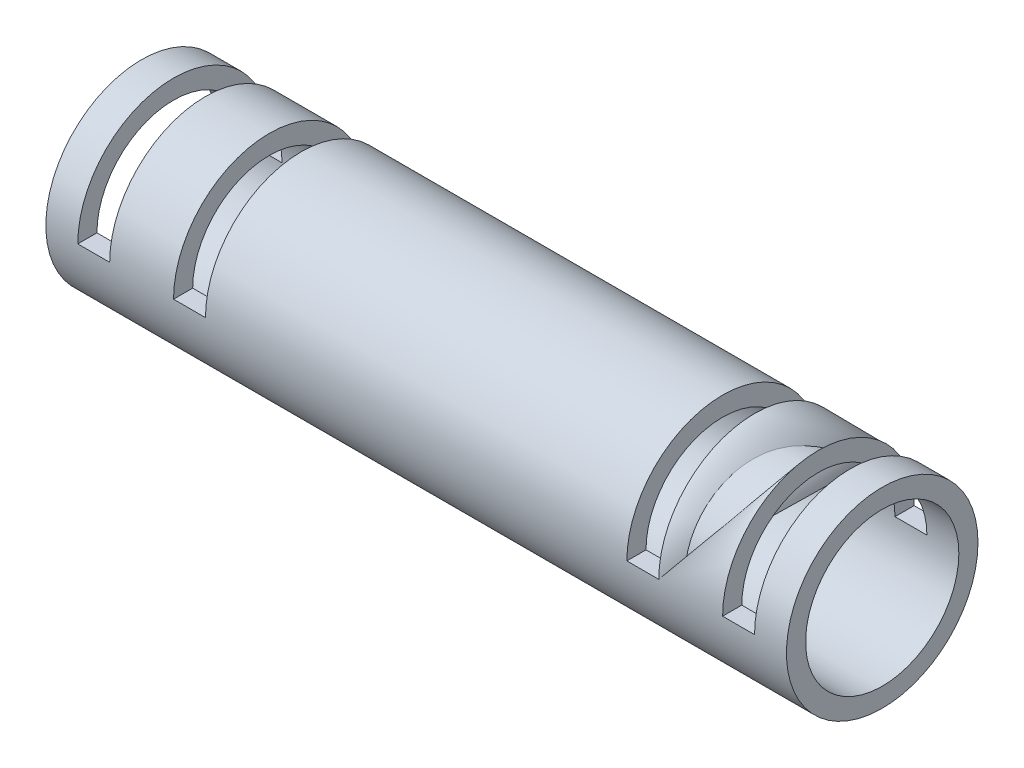
SolidWorks part; units mm, degrees
material "CA"
ref_plane "Front Plane" through (0, 0, 0) normal (0, 0, 1) x (1, 0, 0)
ref_plane "Top Plane" through (0, 0, 0) normal (0, 1, 0) x (1, 0, 0)
ref_plane "Right Plane" through (0, 0, 0) normal (1, 0, 0) x (0, 0, -1)
sketch "Sketch2" plane through (0, 0, 0) normal (1, 0, 0) x (0, 0, -1)
  circle A0 centre (0, 0) radius 7.5
  circle A1 centre (0, 0) radius 6
  dimension "D2" = 15
  dimension "D1" = 1.5
extrude "Boss-Extrude1" add sketch "Sketch2" along normal mid plane 58
sketch "Sketch4" plane through (0, 0, 0) normal (0, 1, 0) x (1, 0, 0)
  line L0 (29, 7.5) -> (-29, 7.5) construction
  line L1 (26.5, 7.5) -> (24, 7.5)
  line L2 (26.5, 7.5) -> (26.5, -7.5)
  line L3 (26.5, -7.5) -> (24, -7.5)
  line L4 (24, 7.5) -> (24, -7.5)
  line L5 (-29, -7.5) -> (29, -7.5) construction
  line L6 (0, 5.5425) -> (0, -3.4354) construction
  line L7 (19, 7.5) -> (16.5, 7.5)
  line L8 (16.5, 7.5) -> (16.5, -7.5)
  line L9 (19, -7.5) -> (16.5, -7.5)
  line L10 (19, 7.5) -> (19, -7.5)
  line L11 (-19, 7.5) -> (-16.5, 7.5)
  line L12 (-16.5, 7.5) -> (-16.5, -7.5)
  line L13 (-19, -7.5) -> (-16.5, -7.5)
  line L14 (-19, 7.5) -> (-19, -7.5)
  line L15 (-26.5, 7.5) -> (-26.5, -7.5)
  line L16 (-26.5, -7.5) -> (-24, -7.5)
  line L17 (-24, 7.5) -> (-24, -7.5)
  line L18 (-26.5, 7.5) -> (-24, 7.5)
  line L19 (29, -7.5) -> (29, 7.5) construction
  dimension "D2" = 2.5
  dimension "D3" = 2.5
  dimension "D4" = 5
  dimension "D1" = 2
extrude "Cut-Extrude1" cut sketch "Sketch4" along normal up to next
